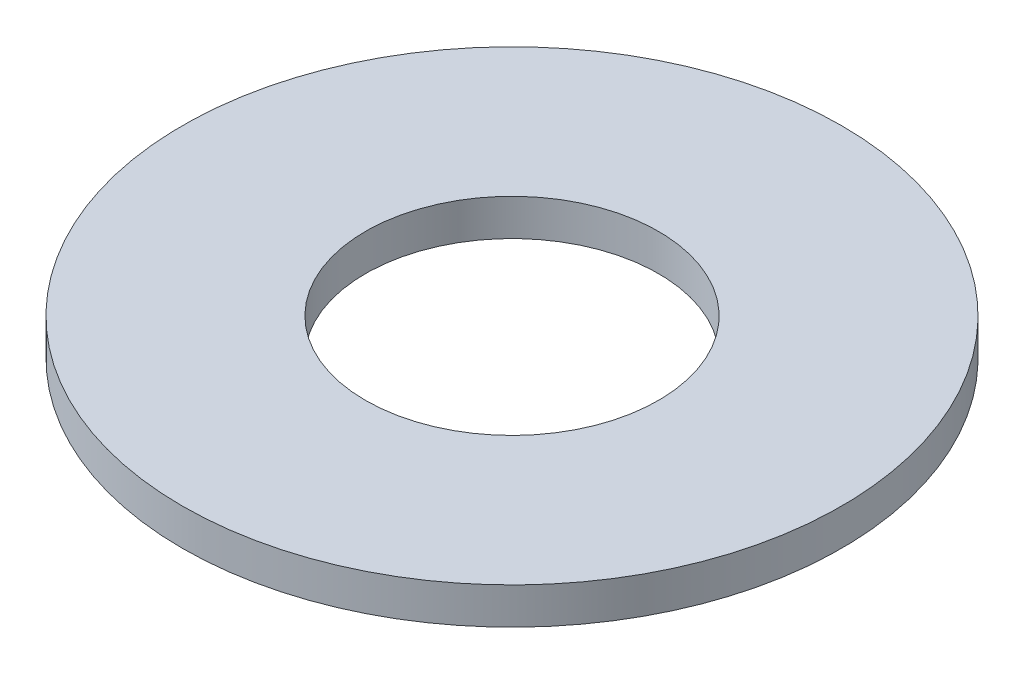
SolidWorks part; units mm, degrees
material "AISI 304"
ref_plane "前视基准面" through (0, 0, 0) normal (0, 0, 1) x (1, 0, 0)
ref_plane "上视基准面" through (0, 0, 0) normal (0, 1, 0) x (1, 0, 0)
ref_plane "右视基准面" through (0, 0, 0) normal (1, 0, 0) x (0, 0, -1)
other "Configuration Table"
sketch "草图1" plane through (0, 0, 0) normal (0, 1, 0) x (1, 0, 0)
  circle A0 centre (0, 0) radius 4.5
  circle A1 centre (0, 0) radius 2
  dimension "D1" = 4
  dimension "D2" = 9
extrude "凸台-拉伸1" add sketch "草图1" along normal blind 0.5
